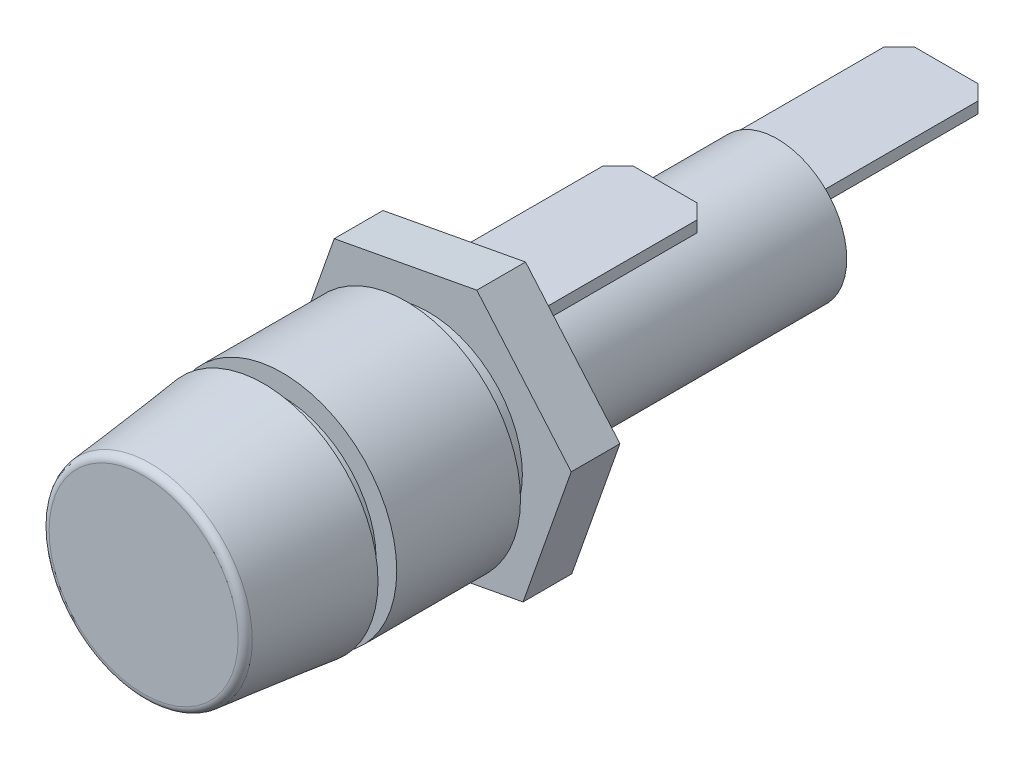
SolidWorks part; units mm, degrees
ref_plane "Front" through (0, 0, 0) normal (0, 0, 1) x (1, 0, 0)
ref_plane "Top" through (0, 0, 0) normal (0, 1, 0) x (1, 0, 0)
ref_plane "Side" through (0, 0, 0) normal (1, 0, 0) x (0, 0, -1)
sketch "Sketch1" plane through (0, 0, 0) normal (0, 1, 0) x (1, 0, 0)
  line L0 (0, 0) -> (0, 67.31) construction
  line L1 (0, -17.78) -> (6.858, -17.78)
  line L2 (6.858, -17.78) -> (7.747, -9.652)
  line L3 (7.747, -9.652) -> (6.35, -9.652)
  line L4 (6.35, -9.652) -> (6.35, -8.382)
  line L5 (6.35, -8.382) -> (7.747, -8.382)
  line L6 (7.747, -8.382) -> (7.747, 0)
  line L7 (7.747, 0) -> (6.35, 0)
  line L8 (6.35, 0) -> (6.35, 6.096)
  line L9 (6.35, 6.096) -> (4.699, 6.096)
  line L10 (4.699, 6.096) -> (4.699, 25.146)
  line L11 (4.699, 25.146) -> (0, 25.146)
  line L12 (0, 25.146) -> (0, -17.78)
  dimension "D1" = 13.716
  dimension "D2" = 15.494
  dimension "D3" = 1.27
  dimension "D4" = 12.7
  dimension "D5" = 12.7
  dimension "D6" = 9.398
  dimension "D7" = 19.05
  dimension "D8" = 6.096
  dimension "D9" = 8.382
  dimension "D10" = 8.128
revolve "Base-Revolve" add sketch "Sketch1" angle 360 about L0
ref_plane "Plane1" through (0, 0, -4.826) normal (0, 0, -1) x (-1, 0, 0)
sketch "Sketch2" plane through (0, 0, -4.826) normal (0, 0, -1) x (-1, 0, 0)
  line L1 (-6.3943, -7.46) -> (3.2634, -9.2676)
  line L2 (3.2634, -9.2676) -> (9.6576, -1.8076)
  line L3 (9.6576, -1.8076) -> (6.3943, 7.46)
  line L4 (6.3943, 7.46) -> (-3.2634, 9.2676)
  line L5 (-3.2634, 9.2676) -> (-9.6576, 1.8076)
  line L6 (-9.6576, 1.8076) -> (-6.3943, -7.46)
  circle A0 centre (0, 0) radius 8.509 construction
extrude "Boss-Extrude1" add sketch "Sketch2" against normal blind 3.302
fillet "Fillet1" radius 0.508
sketch "Sketch3" plane through (0, 0, -25.146) normal (0, 0, -1) x (-1, 0, 0)
  line L0 (0, 0) -> (0, 7.62) construction
  line L1 (-3.175, 2.54) -> (3.175, 2.54)
  line L2 (-3.175, 2.54) -> (-3.175, 3.302)
  line L3 (-3.175, 3.302) -> (3.175, 3.302)
  line L4 (3.175, 2.54) -> (3.175, 3.302)
  dimension "D1" = 0.762
  dimension "D2" = 6.35
  dimension "D3" = 2.54
extrude "Boss-Extrude2" add sketch "Sketch3" along normal blind 11.43
sketch "Sketch4" plane through (-0.2176, 1.7483, -6.096) normal (0, 0, -1) x (-1, 0, 0)
  line L0 (-0.2176, -1.7483) -> (-0.2176, 7.62) construction
  line L1 (-3.3926, 3.3317) -> (2.9574, 3.3317)
  line L2 (-3.3926, 3.3317) -> (-3.3926, 4.0937)
  line L3 (-3.3926, 4.0937) -> (2.9574, 4.0937)
  line L4 (2.9574, 3.3317) -> (2.9574, 4.0937)
  dimension "D1" = 0.762
  dimension "D2" = 6.35
  dimension "D3" = 5.08
extrude "Boss-Extrude3" add sketch "Sketch4" along normal blind 11.43
chamfer "Chamfer1" distance 1.016 angle 45
